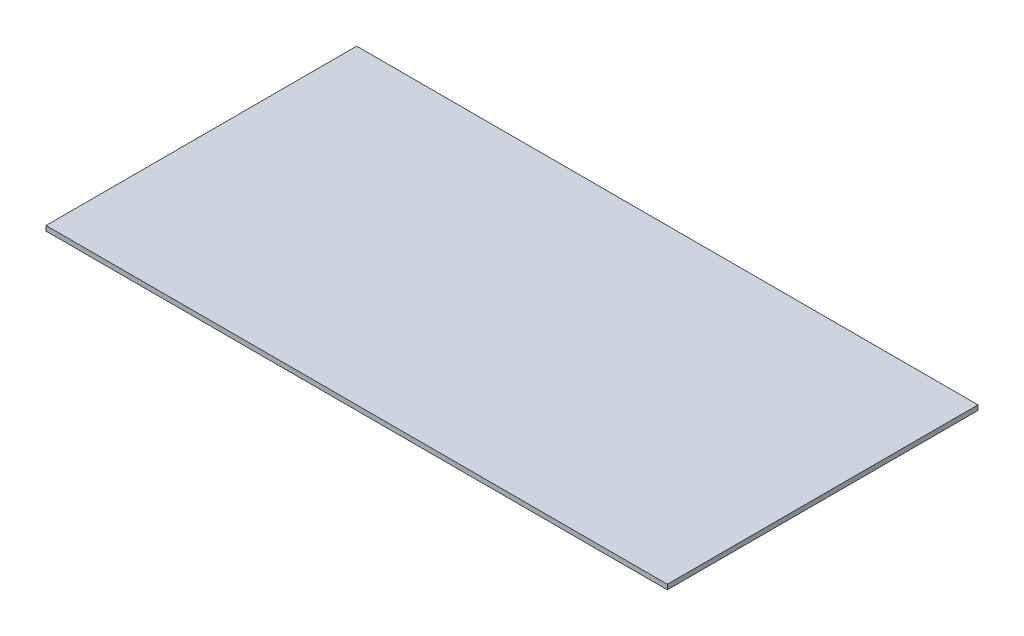
SolidWorks part; units mm, degrees
ref_plane "Front Plane" through (0, 0, 0) normal (0, 0, 1) x (1, 0, 0)
ref_plane "Top Plane" through (0, 0, 0) normal (0, 1, 0) x (1, 0, 0)
ref_plane "Right Plane" through (0, 0, 0) normal (1, 0, 0) x (0, 0, -1)
sketch "Sketch1" plane through (0, 0, 0) normal (0, 1, 0) x (1, 0, 0)
  line L1 (0, 0) -> (2438.4, 0)
  line L2 (0, 0) -> (0, 1219.2)
  line L3 (0, 1219.2) -> (2438.4, 1219.2)
  line L4 (2438.4, 0) -> (2438.4, 1219.2)
  dimension "D1" = 2438.4
  dimension "D2" = 1219.2
extrude "Boss-Extrude1" add sketch "Sketch1" against normal blind 19.05
